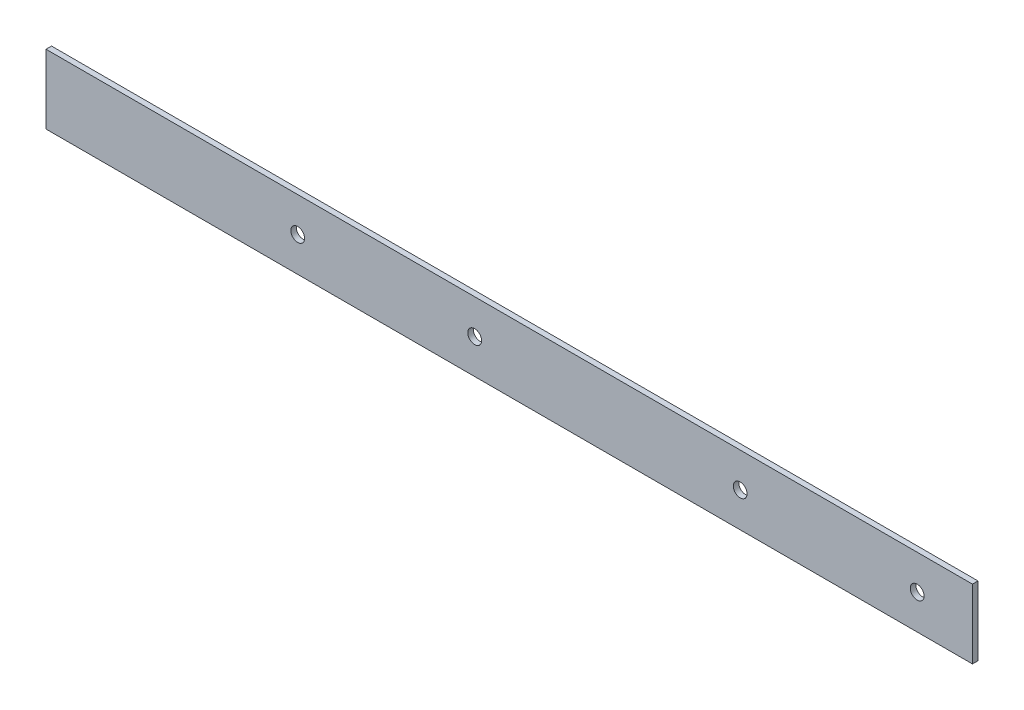
SolidWorks part; units mm, degrees
material "环氧树脂,未充填"
ref_plane "前视基准面" through (0, 0, 0) normal (0, 0, 1) x (1, 0, 0)
ref_plane "上视基准面" through (0, 0, 0) normal (0, 1, 0) x (1, 0, 0)
ref_plane "右视基准面" through (0, 0, 0) normal (1, 0, 0) x (0, 0, -1)
sketch "草图1" plane through (0, 0, 0) normal (0, 0, 1) x (1, 0, 0)
  line L1 (-167.5, 12.5) -> (167.5, 12.5)
  line L2 (-167.5, 12.5) -> (-167.5, -12.5)
  line L3 (-167.5, -12.5) -> (167.5, -12.5)
  line L4 (167.5, 12.5) -> (167.5, -12.5)
  line L5 (-167.5, 12.5) -> (167.5, -12.5) construction
  line L6 (-167.5, -12.5) -> (167.5, 12.5) construction
  point P0 (0, 0)
  dimension "D1" = 25
  dimension "D2" = 335
extrude "凸台-拉伸1" add sketch "草图1" along normal blind 2
sketch "草图2" plane through (0, 0, 2) normal (0, 0, 1) x (1, 0, 0)
  line L0 (-167.5, 0) -> (167.5, 0) construction
  line L1 (-167.5, 12.5) -> (-167.5, -12.5) construction
  line L2 (167.5, -12.5) -> (167.5, 12.5) construction
  circle A0 centre (-76.5, 0) radius 2.5
  circle A1 centre (-12.5, 0) radius 2.5
  circle A2 centre (83.5, 0) radius 2.5
  circle A3 centre (147.5, 0) radius 2.5
  dimension "D1" = 5
  dimension "D3" = 64
  dimension "D2" = 91
  dimension "D4" = 2
extrude "切除-拉伸1" cut sketch "草图2" against normal through all
